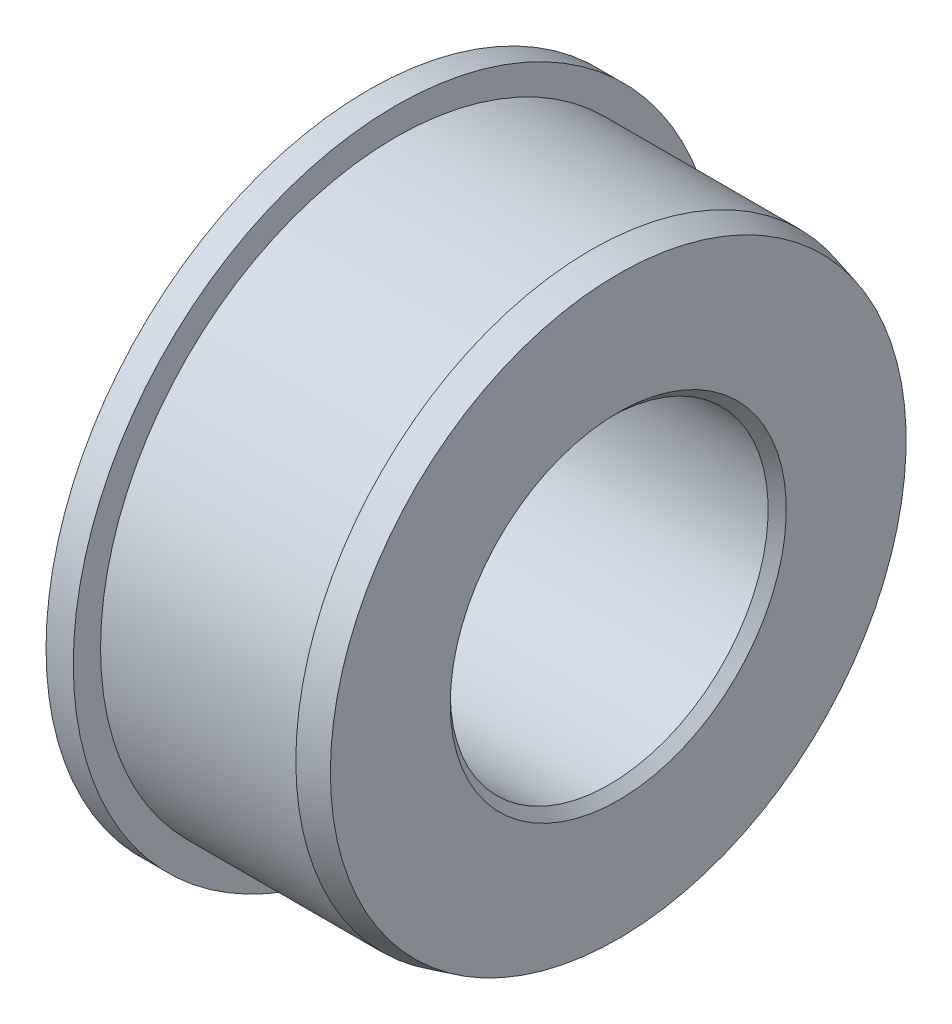
SolidWorks part; units mm, degrees
material "Алюминиевая бронза"
ref_plane "Спереди" through (0, 0, 0) normal (0, 0, 1) x (1, 0, 0)
ref_plane "Сверху" through (0, 0, 0) normal (0, 1, 0) x (1, 0, 0)
ref_plane "Справа" through (0, 0, 0) normal (1, 0, 0) x (0, 0, -1)
sketch "Эскиз1" plane through (0, 0, 0) normal (0, 0, 1) x (1, 0, 0)
  line L0 (0, 0) -> (38.4545, 0) construction
  line L1 (0, 18.5) -> (0, 35.5)
  line L2 (0, 35.5) -> (3, 35.5)
  line L3 (3, 35.5) -> (3, 32.5)
  line L4 (3, 32.5) -> (24.5, 32.5)
  line L5 (27.5, 31.6962) -> (27.5, 18.5)
  line L6 (26.5, 17.5) -> (1, 17.5)
  line L7 (27.5, 18.5) -> (26.5, 17.5)
  line L8 (24.5, 32.5) -> (27.5, 31.6962)
  line L9 (1, 17.5) -> (0, 18.5)
  point P3 (0, 17.5)
  point P8 (27.5, 32.5)
  point P9 (27.5, 17.5)
  dimension "D1" = 3
  dimension "D2" = 24.5
  dimension "D3" = 65
  dimension "D4" = 71
  dimension "D5" = 35
  dimension "D6" = 1
  dimension "D7" = 45
  dimension "D8" = 3
  dimension "D9" = 15
  dimension "D10" = 1
  dimension "D11" = 45
revolve "Повернуть1" add sketch "Эскиз1" angle 360 about L0
